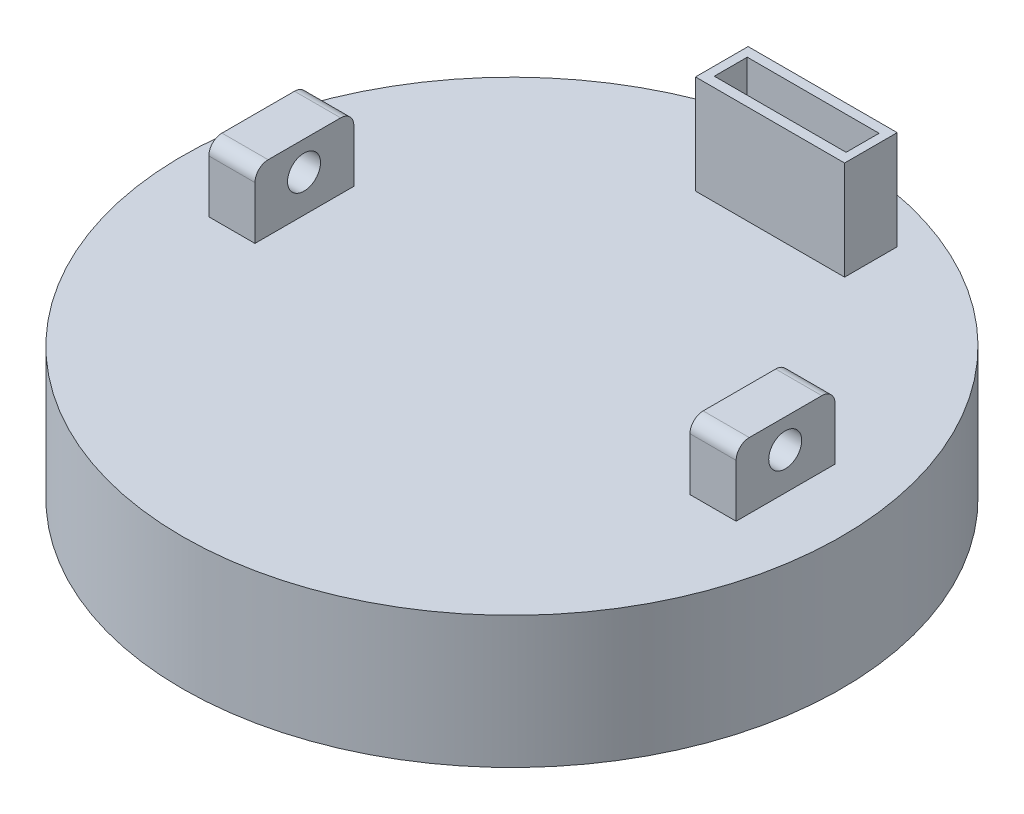
SolidWorks part; units mm, degrees
material "1.4000 (X6Cr13)"
ref_plane "前视" through (0, 0, 0) normal (0, 0, 1) x (1, 0, 0)
ref_plane "上视" through (0, 0, 0) normal (0, 1, 0) x (1, 0, 0)
ref_plane "右视" through (0, 0, 0) normal (1, 0, 0) x (0, 0, -1)
sketch "草图2" plane through (0, 0, 0) normal (0, 1, 0) x (1, 0, 0)
  circle A0 centre (5.13, 5.9877) radius 50
  dimension "D1" = 100
extrude "凸台-拉伸1" add sketch "草图2" along normal blind 20 contours A0
sketch "草图3" plane through (0, 20, 0) normal (0, 1, 0) x (1, 0, 0)
  line L1 (-34.87, 15) -> (-27.87, 15)
  line L2 (-34.87, 15) -> (-34.87, 0)
  line L3 (-34.87, 0) -> (-27.87, 0)
  line L4 (-27.87, 15) -> (-27.87, 0)
  line L5 (38.13, 15) -> (45.13, 15)
  line L6 (38.13, 15) -> (38.13, 0)
  line L7 (38.13, 0) -> (45.13, 0)
  line L8 (45.13, 15) -> (45.13, 0)
  circle A0 centre (5.13, 5.9877) radius 50 construction
  dimension "D1" = 15
  dimension "D2" = 7
  dimension "D3" = 15
  dimension "D4" = 7
  dimension "D5" = 40
  dimension "D6" = 40
extrude "凸台-拉伸2" add sketch "草图3" along normal blind 10
sketch "草图5" plane through (-34.87, 0, 0) normal (-1, 0, 0) x (0, 0, 1)
  line L0 (-7.4453, 37.2764) -> (-7.4453, 8.4529) construction
  circle A0 centre (-7.4453, 25.6528) radius 2.5
  dimension "D1" = 5
extrude "切除-拉伸1" cut sketch "草图5" against normal through all
sketch "草图7" plane through (0, 20, 0) normal (0, 1, 0) x (1, 0, 0)
  line L1 (0, 46.818) -> (20, 46.818)
  line L2 (0, 46.818) -> (0, 41.818)
  line L3 (0, 41.818) -> (20, 41.818)
  line L4 (20, 46.818) -> (20, 41.818)
  line L5 (-1.3327, 40.2973) -> (21.2869, 40.2973)
  line L6 (-1.3327, 40.2973) -> (-1.3327, 48.2807)
  line L7 (-1.3327, 48.2807) -> (21.2869, 48.2807)
  line L8 (21.2869, 40.2973) -> (21.2869, 48.2807)
  dimension "D1" = 20
  dimension "D2" = 5
extrude "凸台-拉伸3" add sketch "草图7" along normal blind 15
sketch "草图8" plane through (0, 0, 0) normal (0, -1, 0) x (1, 0, 0)
  line L1 (-1.3327, -40.2973) -> (21.2869, -40.2973)
  line L2 (-1.3327, -40.2973) -> (-1.3327, -48.2807)
  line L3 (-1.3327, -48.2807) -> (21.2869, -48.2807)
  line L4 (21.2869, -40.2973) -> (21.2869, -48.2807)
extrude "切除-拉伸2" cut sketch "草图8" against normal blind 5
fillet "圆角1" radius 2 1 edges at (-31.37, 30, -15)
fillet "圆角2" radius 2 3 edges at (41.63, 30, -15) (41.63, 30, 0) (-31.37, 30, 0)
